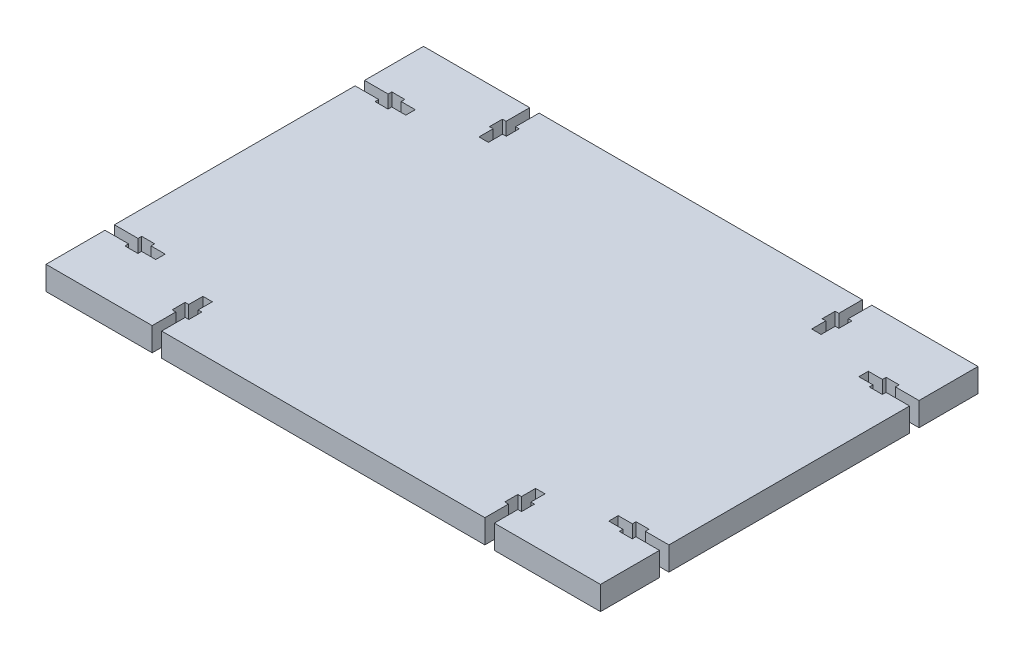
SolidWorks part; units mm, degrees
ref_plane "Front Plane" through (0, 0, 0) normal (0, 0, 1) x (1, 0, 0)
ref_plane "Top Plane" through (0, 0, 0) normal (0, 1, 0) x (1, 0, 0)
ref_plane "Right Plane" through (0, 0, 0) normal (1, 0, 0) x (0, 0, -1)
sketch "Sketch1" plane through (0, 0, 0) normal (0, 0, 1) x (1, 0, 0)
  line L1 (0, 0) -> (235, 0)
  line L2 (0, 0) -> (0, 10)
  line L3 (0, 10) -> (235, 10)
  line L4 (235, 0) -> (235, 10)
  dimension "D1" = 10
  dimension "D2" = 235
extrude "Boss-Extrude1" add sketch "Sketch1" along normal blind 160
sketch "Esquisse2" plane through (0, 0, 0) normal (0, -1, 0) x (1, 0, 0)
  line L0 (0, 135) -> (10, 135)
  line L1 (0, 160) -> (0, 0) construction
  line L2 (10, 135) -> (10, 136.55)
  line L3 (10, 136.55) -> (15.5, 136.55)
  line L4 (15.5, 136.55) -> (15.5, 135)
  line L5 (15.5, 135) -> (21.5, 135)
  line L6 (21.5, 135) -> (21.5, 131)
  line L7 (0, 131) -> (0, 135)
  line L8 (0, 133) -> (21.5, 133) construction
  line L9 (15.5, 131) -> (21.5, 131)
  line L10 (15.5, 129.45) -> (15.5, 131)
  line L11 (10, 129.45) -> (15.5, 129.45)
  line L12 (10, 131) -> (10, 129.45)
  line L13 (0, 131) -> (10, 131)
  line L14 (0, 80) -> (34.6012, 80) construction
  line L15 (0, 160) -> (235, 160) construction
  line L16 (0, 27) -> (21.5, 27) construction
  line L17 (0, 29) -> (10, 29)
  line L18 (10, 29) -> (10, 30.55)
  line L19 (10, 30.55) -> (15.5, 30.55)
  line L20 (15.5, 30.55) -> (15.5, 29)
  line L21 (15.5, 29) -> (21.5, 29)
  line L22 (0, 29) -> (0, 25)
  line L23 (21.5, 25) -> (21.5, 29)
  line L24 (15.5, 25) -> (21.5, 25)
  line L25 (15.5, 23.45) -> (15.5, 25)
  line L26 (10, 23.45) -> (15.5, 23.45)
  line L27 (10, 25) -> (10, 23.45)
  line L28 (0, 25) -> (10, 25)
  line L29 (117.5, 160) -> (117.5, 129.475) construction
  line L30 (235, 27) -> (213.5, 27) construction
  line L31 (235, 80) -> (200.3988, 80) construction
  line L32 (235, 133) -> (213.5, 133) construction
  line L33 (235, 25) -> (225, 25)
  line L34 (225, 25) -> (225, 23.45)
  line L35 (225, 23.45) -> (219.5, 23.45)
  line L36 (219.5, 23.45) -> (219.5, 25)
  line L37 (219.5, 25) -> (213.5, 25)
  line L38 (213.5, 25) -> (213.5, 29)
  line L39 (235, 29) -> (235, 25)
  line L40 (219.5, 29) -> (213.5, 29)
  line L41 (219.5, 30.55) -> (219.5, 29)
  line L42 (225, 30.55) -> (219.5, 30.55)
  line L43 (225, 29) -> (225, 30.55)
  line L44 (235, 29) -> (225, 29)
  line L45 (235, 131) -> (225, 131)
  line L46 (225, 131) -> (225, 129.45)
  line L47 (225, 129.45) -> (219.5, 129.45)
  line L48 (219.5, 129.45) -> (219.5, 131)
  line L49 (219.5, 131) -> (213.5, 131)
  line L50 (235, 131) -> (235, 135)
  line L51 (213.5, 135) -> (213.5, 131)
  line L52 (219.5, 135) -> (213.5, 135)
  line L53 (219.5, 136.55) -> (219.5, 135)
  line L54 (225, 136.55) -> (219.5, 136.55)
  line L55 (225, 135) -> (225, 136.55)
  line L56 (235, 135) -> (225, 135)
  dimension "D1" = 5.5
  dimension "D2" = 10
  dimension "D3" = 6
  dimension "D4" = 2
  dimension "D5" = 7.1
  dimension "D6" = 4
  dimension "D7" = 25
extrude "Enlèv. mat.-Extru.2" cut sketch "Esquisse2" against normal blind 10
sketch "Esquisse3" plane through (0, 0, 0) normal (0, -1, 0) x (1, 0, 0)
  line L0 (0, 80) -> (235, 80) construction
  line L1 (0, 131) -> (0, 29) construction
  line L2 (235, 131) -> (235, 29) construction
  line L3 (117.5, 160) -> (117.5, 0) construction
  line L4 (0, 160) -> (235, 160) construction
  line L5 (0, 0) -> (235, 0) construction
  line L6 (45, 160) -> (45, 150)
  line L7 (45, 150) -> (43.45, 150)
  line L8 (43.45, 150) -> (43.45, 144.5)
  line L10 (49, 144.5) -> (49, 138.5)
  line L11 (49, 138.5) -> (45, 138.5)
  line L12 (47, 138.5) -> (47, 160) construction
  line L13 (45, 160) -> (49, 160)
  line L14 (45, 144.5) -> (45, 138.5)
  line L16 (50.55, 150) -> (50.55, 144.5)
  line L17 (49, 150) -> (50.55, 150)
  line L18 (49, 160) -> (49, 150)
  line L19 (43.45, 144.5) -> (45, 144.5)
  line L20 (49, 144.5) -> (50.55, 144.5)
  line L21 (0, 160) -> (0, 135) construction
  line L32 (188, 138.5) -> (188, 160) construction
  line L33 (186, 160) -> (186, 150)
  line L34 (186, 150) -> (184.45, 150)
  line L35 (184.45, 150) -> (184.45, 144.5)
  line L36 (190, 144.5) -> (190, 138.5)
  line L37 (186, 144.5) -> (186, 138.5)
  line L38 (191.55, 150) -> (191.55, 144.5)
  line L39 (190, 150) -> (191.55, 150)
  line L40 (190, 160) -> (190, 150)
  line L41 (184.45, 144.5) -> (186, 144.5)
  line L42 (190, 144.5) -> (191.55, 144.5)
  line L49 (190, 160) -> (186, 160)
  line L50 (186, 138.5) -> (190, 138.5)
  line L55 (188, 21.5) -> (188, 0) construction
  line L56 (47, 21.5) -> (47, 0) construction
  line L57 (190, 0) -> (190, 10)
  line L58 (190, 10) -> (191.55, 10)
  line L59 (191.55, 10) -> (191.55, 15.5)
  line L60 (186, 15.5) -> (186, 21.5)
  line L61 (186, 21.5) -> (190, 21.5)
  line L62 (190, 0) -> (186, 0)
  line L63 (190, 15.5) -> (190, 21.5)
  line L64 (184.45, 10) -> (184.45, 15.5)
  line L65 (186, 10) -> (184.45, 10)
  line L66 (186, 0) -> (186, 10)
  line L67 (191.55, 15.5) -> (190, 15.5)
  line L68 (186, 15.5) -> (184.45, 15.5)
  line L79 (49, 0) -> (49, 10)
  line L80 (49, 10) -> (50.55, 10)
  line L81 (50.55, 10) -> (50.55, 15.5)
  line L82 (45, 15.5) -> (45, 21.5)
  line L83 (49, 15.5) -> (49, 21.5)
  line L84 (43.45, 10) -> (43.45, 15.5)
  line L85 (45, 10) -> (43.45, 10)
  line L86 (45, 0) -> (45, 10)
  line L87 (50.55, 15.5) -> (49, 15.5)
  line L88 (45, 15.5) -> (43.45, 15.5)
  line L95 (45, 0) -> (49, 0)
  line L96 (49, 21.5) -> (45, 21.5)
  dimension "D1" = 2
  dimension "D2" = 5.5
  dimension "D3" = 10
  dimension "D4" = 6
  dimension "D5" = 7.1
  dimension "D6" = 4
  dimension "D7" = 47
extrude "Enlèv. mat.-Extru.3" cut sketch "Esquisse3" against normal blind 10
